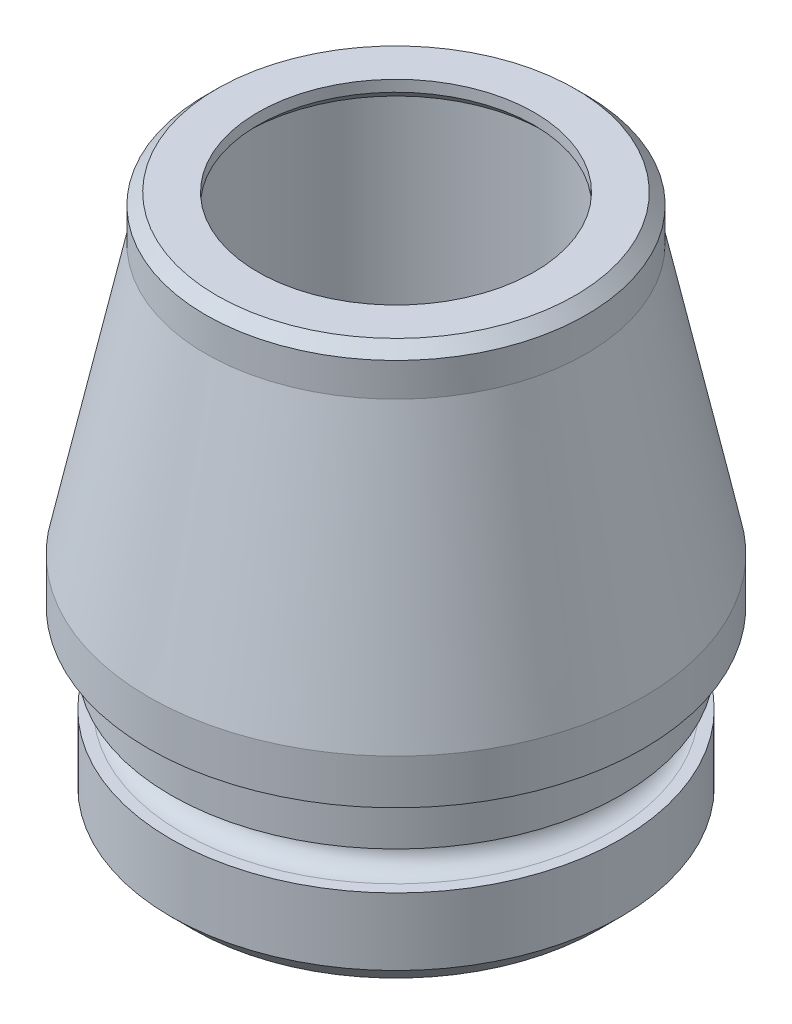
SolidWorks part; units mm, degrees
ref_plane "정면" through (0, 0, 0) normal (0, 0, 1) x (1, 0, 0)
ref_plane "윗면" through (0, 0, 0) normal (0, 1, 0) x (1, 0, 0)
ref_plane "우측면" through (0, 0, 0) normal (1, 0, 0) x (0, 0, -1)
sketch "스케치1" plane through (0, 0, 0) normal (1, 0, 0) x (0, 0, -1)
  line L0 (0, 0) -> (7.1, 0) construction
  line L1 (7.1, 0) -> (7.1, 23)
  line L2 (6.175, 24) -> (8.5, 24)
  line L3 (8.5, 24) -> (8.5, 22)
  line L4 (8.5, 22) -> (11.05, 10)
  line L5 (11.05, 10) -> (11.05, 8)
  line L6 (10.05, 0) -> (7.1, 0)
  line L7 (9.55, 5.7) -> (10.05, 5.7)
  line L8 (9.55, 4) -> (10.05, 4)
  line L9 (0, 0) -> (0, 30) construction
  line L10 (11.05, 8) -> (10.05, 8)
  line L11 (10.05, 8) -> (10.05, 5.7)
  line L12 (10.05, 4) -> (10.05, 0)
  line L13 (7.1, 23) -> (6.175, 23)
  line L14 (6.175, 23) -> (6.175, 24)
  arc A0 (9.55, 5.7) -> (9.55, 4) centre (9.55, 4.85) ccw
  dimension "D10" = 0.85
  dimension "D1" = 2
  dimension "D2" = 2
  dimension "D3" = 4
  dimension "D4" = 12
  dimension "D5" = 10.05
  dimension "D6" = 7.1
  dimension "D7" = 1
  dimension "D8" = 8.5
  dimension "D9" = 10
  dimension "D11" = 0.5
  dimension "D12" = 30
  dimension "D13" = 12.35
  dimension "D15" = 1
revolve "회전1" add sketch "스케치1" angle 360 about L9
chamfer "모따기1" distance 1 angle 45 1 edges at (0, 0, -10.05)
chamfer "모따기2" distance 0.5 angle 45 1 edges at (0, 24, -8.5)
fillet "필렛1" radius 0.3 1 edges at (0, 0, -7.1)
chamfer "모따기3" distance 0.5 angle 45 1 edges at (0, 23, -6.175)
